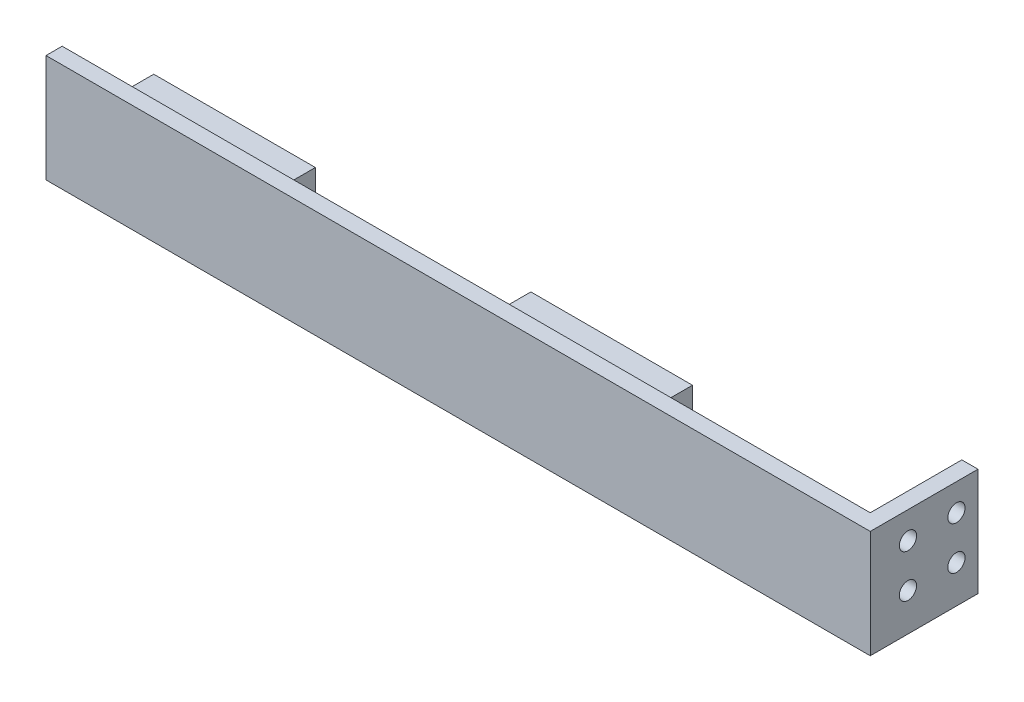
SolidWorks part; units mm, degrees
ref_plane "Front Plane" through (0, 0, 0) normal (0, 0, 1) x (1, 0, 0)
ref_plane "Top Plane" through (0, 0, 0) normal (0, 1, 0) x (1, 0, 0)
ref_plane "Right Plane" through (0, 0, 0) normal (1, 0, 0) x (0, 0, -1)
sketch "Sketch1" plane through (0, 0, 0) normal (1, 0, 0) x (0, 0, -1)
  line L1 (-88.2455, 0.4988) -> (-108.2455, 0.4988)
  line L2 (-88.2455, 0.4988) -> (-88.2455, -19.5012)
  line L3 (-88.2455, -19.5012) -> (-108.2455, -19.5012)
  line L4 (-108.2455, 0.4988) -> (-108.2455, -19.5012)
  dimension "D1" = 20
  dimension "D2" = 20
extrude "Boss-Extrude1" add sketch "Sketch1" along normal blind 3
sketch "Sketch2" plane through (0, 0, 0) normal (-1, 0, 0) x (0, 0, 1)
  line L0 (88.2455, 0.4988) -> (108.2455, 0.4988) construction
  line L1 (108.2455, -19.5012) -> (105.2455, -19.5012)
  line L2 (108.2455, -19.5012) -> (108.2455, 0.4988)
  line L3 (108.2455, 0.4988) -> (105.2455, 0.4988)
  line L4 (105.2455, -19.5012) -> (105.2455, 0.4988)
  dimension "D1" = 3
extrude "Boss-Extrude2" add sketch "Sketch2" along normal blind 150
sketch "Sketch3" plane through (0, 0, 0) normal (-1, 0, 0) x (0, 0, 1)
  line L0 (105.2455, 0.4988) -> (105.2455, -19.5012) construction
  line L1 (88.2455, -19.5012) -> (105.2455, -19.5012)
  line L2 (88.2455, -19.5012) -> (88.2455, -16.5012)
  line L3 (88.2455, -16.5012) -> (105.2455, -16.5012)
  line L4 (105.2455, -19.5012) -> (105.2455, -16.5012)
  dimension "D1" = 3
extrude "Boss-Extrude3" add sketch "Sketch3" along normal blind 150
sketch "Sketch4" plane through (3, 0, 0) normal (1, 0, 0) x (0, 0, -1)
  circle A0 centre (-101.2455, -4.5012) radius 1.6
  circle A1 centre (-92.2455, -4.5012) radius 1.6
  circle A2 centre (-92.2455, -12.5012) radius 1.6
  circle A3 centre (-101.2455, -12.5012) radius 1.6
extrude "Cut-Extrude1" cut sketch "Sketch4" against normal blind 3
sketch "Sketch5" plane through (0, -16.5012, 0) normal (0, 1, 0) x (1, 0, 0)
  line L0 (-150, -105.2455) -> (0, -105.2455) construction
  line L1 (-150, -88.2455) -> (-120, -88.2455)
  line L2 (-150, -88.2455) -> (-150, -105.2455)
  line L3 (-150, -105.2455) -> (-120, -105.2455)
  line L4 (-120, -88.2455) -> (-120, -105.2455)
  dimension "D1" = 30
extrude "Boss-Extrude4" add sketch "Sketch5" along normal blind 4
sketch "Sketch6" plane through (0, -16.5012, 0) normal (0, 1, 0) x (1, 0, 0)
  line L0 (-120, -105.2455) -> (0, -105.2455) construction
  line L1 (-80, -105.2455) -> (-50, -105.2455)
  line L2 (-80, -105.2455) -> (-80, -88.2455)
  line L3 (-80, -88.2455) -> (-50, -88.2455)
  line L4 (-50, -105.2455) -> (-50, -88.2455)
  line L5 (-120, -88.2455) -> (0, -88.2455) construction
  line L6 (-150, -88.2455) -> (-150, -105.2455) construction
  dimension "D1" = 30
  dimension "D2" = 70
extrude "Boss-Extrude5" add sketch "Sketch6" along normal blind 4
sketch "Sketch9" plane through (0, -12.5012, 0) normal (0, 1, 0) x (1, 0, 0)
  line L0 (-150, -105.2455) -> (0, -105.2455) construction
  line L1 (-80, -88.2455) -> (-80, -105.2455) construction
  line L2 (-50, -105.2455) -> (-50, -88.2455) construction
  line L3 (-120, -105.2455) -> (-120, -88.2455) construction
  line L4 (-150, -88.2455) -> (-150, -105.2455) construction
  circle A0 centre (-58, -96.7455) radius 2.05
  circle A1 centre (-72, -96.7455) radius 2.1
  circle A2 centre (-128, -96.7455) radius 2.1
  circle A3 centre (-142, -96.7455) radius 2.1
  dimension "D1" = 4.1
  dimension "D2" = 4.2
  dimension "D3" = 4.2
  dimension "D4" = 4.2
  dimension "D5" = 8.5
  dimension "D6" = 8.5
  dimension "D7" = 8
  dimension "D8" = 8
  dimension "D9" = 8.5
  dimension "D10" = 8.5
  dimension "D11" = 8
  dimension "D12" = 8
extrude "Cut-Extrude4" cut sketch "Sketch9" against normal through all
sketch "Sketch10" plane through (0, -19.5012, 0) normal (0, -1, 0) x (1, 0, 0)
  circle A0 centre (-142, 96.7455) radius 4
  circle A1 centre (-128, 96.7455) radius 4
  circle A2 centre (-72, 96.7455) radius 4
  circle A3 centre (-58, 96.7455) radius 4
  dimension "D1" = 8
  dimension "D2" = 8
  dimension "D3" = 8
  dimension "D4" = 8
extrude "Cut-Extrude5" cut sketch "Sketch10" against normal blind 2.5
chamfer "Chamfer3" distance 3 angle 45 2 edges at (-100, -16.5012, 105.2455) (-25, -16.5012, 105.2455)
sketch "Sketch12" plane through (0, -16.5012, 0) normal (0, 1, 0) x (1, 0, 0)
  line L0 (-150, -105.2455) -> (0, -105.2455) construction
  line L1 (-120, -88.2455) -> (-116.9, -88.2455)
  line L2 (-120, -88.2455) -> (-120, -105.2455)
  line L3 (-120, -105.2455) -> (-116.9, -105.2455)
  line L4 (-116.9, -88.2455) -> (-116.9, -105.2455)
  line L6 (-80, -88.2455) -> (-83.1, -88.2455)
  line L7 (-80, -88.2455) -> (-80, -105.2455)
  line L8 (-80, -105.2455) -> (-83.1, -105.2455)
  line L9 (-83.1, -88.2455) -> (-83.1, -105.2455)
  line L10 (-50, -88.2455) -> (-46.9, -88.2455)
  line L11 (-50, -88.2455) -> (-50, -105.2455)
  line L12 (-50, -105.2455) -> (-46.9, -105.2455)
  line L13 (-46.9, -88.2455) -> (-46.9, -105.2455)
  dimension "D1" = 3.1
  dimension "D2" = 3.1
  dimension "D3" = 3.1
extrude "Cut-Extrude7" cut sketch "Sketch12" along normal blind 3
